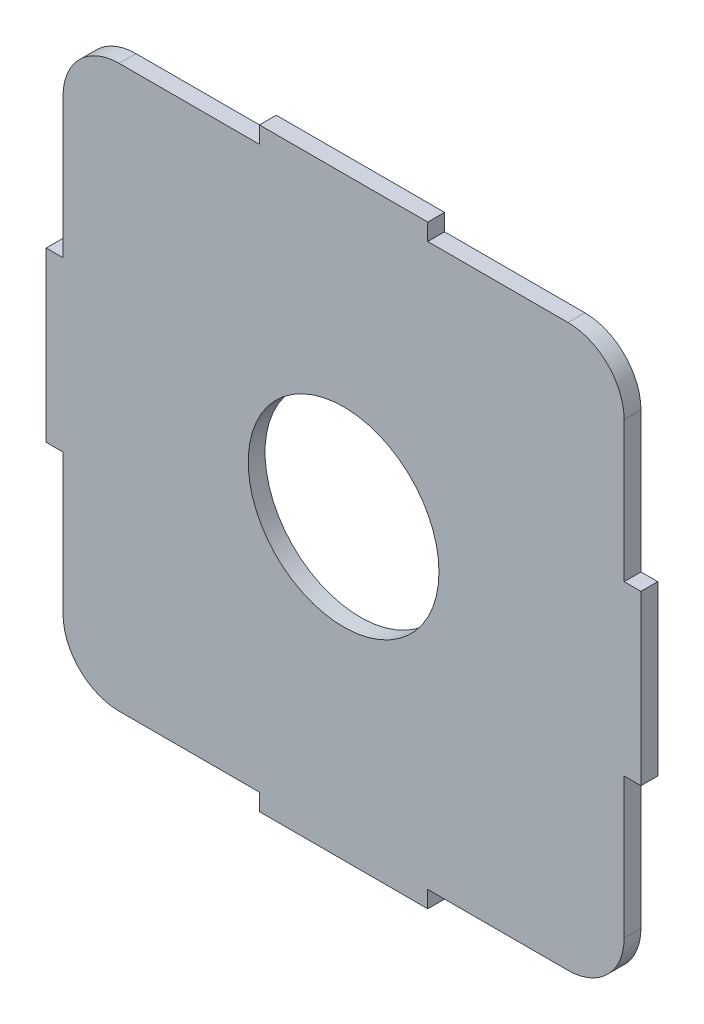
SolidWorks part; units mm, degrees
ref_plane "Plan de face" through (0, 0, 0) normal (0, 0, 1) x (1, 0, 0)
ref_plane "Plan de dessus" through (0, 0, 0) normal (0, 1, 0) x (1, 0, 0)
ref_plane "Plan de droite" through (0, 0, 0) normal (1, 0, 0) x (0, 0, -1)
sketch "Esquisse1" plane through (0, 0, 0) normal (0, 0, 1) x (1, 0, 0)
  line L0 (0, 0) -> (0, 35)
  line L1 (0, 100) -> (35, 100)
  line L2 (100, 100) -> (100, 65)
  line L3 (100, 0) -> (65, 0)
  line L4 (-3, 35) -> (-3, 65)
  line L5 (-3, 65) -> (0, 65)
  line L6 (-3, 35) -> (0, 35)
  line L7 (35, 103) -> (65, 103)
  line L8 (65, 103) -> (65, 100)
  line L9 (35, 103) -> (35, 100)
  line L10 (103, 65) -> (103, 35)
  line L11 (103, 35) -> (100, 35)
  line L12 (103, 65) -> (100, 65)
  line L13 (65, -3) -> (35, -3)
  line L14 (35, -3) -> (35, 0)
  line L15 (65, -3) -> (65, 0)
  line L16 (65, 100) -> (100, 100)
  line L17 (100, 35) -> (100, 0)
  line L18 (35, 0) -> (0, 0)
  line L19 (0, 65) -> (0, 100)
  point P8 (-3, 50)
  point P25 (50, 50)
  dimension "D1" = 100
  dimension "D3" = 3
  dimension "D4" = 30
  dimension "D5" = 4
extrude "Boss.-Extru.1" add sketch "Esquisse1" along normal blind 3
sketch "Esquisse3" plane through (0, 0, 3) normal (0, 0, 1) x (1, 0, 0)
  line L0 (100, 100) -> (0, 0) construction
  line L1 (0, 100) -> (100, 0) construction
sketch "Esquisse2" plane through (0, 0, 3) normal (0, 0, 1) x (1, 0, 0)
  line L0 (100, 100) -> (0, 0) construction
  circle A0 centre (50, 50) radius 17
  point P2 (46.1007, 50.0722)
  point P3 (47.8337, 50.5055)
  point P4 (40.4251, 42.6622)
  point P5 (45.7151, 53.3386)
  point P6 (50, 50)
  point P10 (82.5, 17.5)
  dimension "D1" = 34
extrude "Enlèv. mat.-Extru.1" cut sketch "Esquisse2" against normal up to surface (3 mm away) up to face at (50, 50, 0)
fillet "Congé1" radius 10 4 edges at (0, 0, 1.5) (100, 0, 1.5) (100, 100, 1.5) (0, 100, 1.5)
